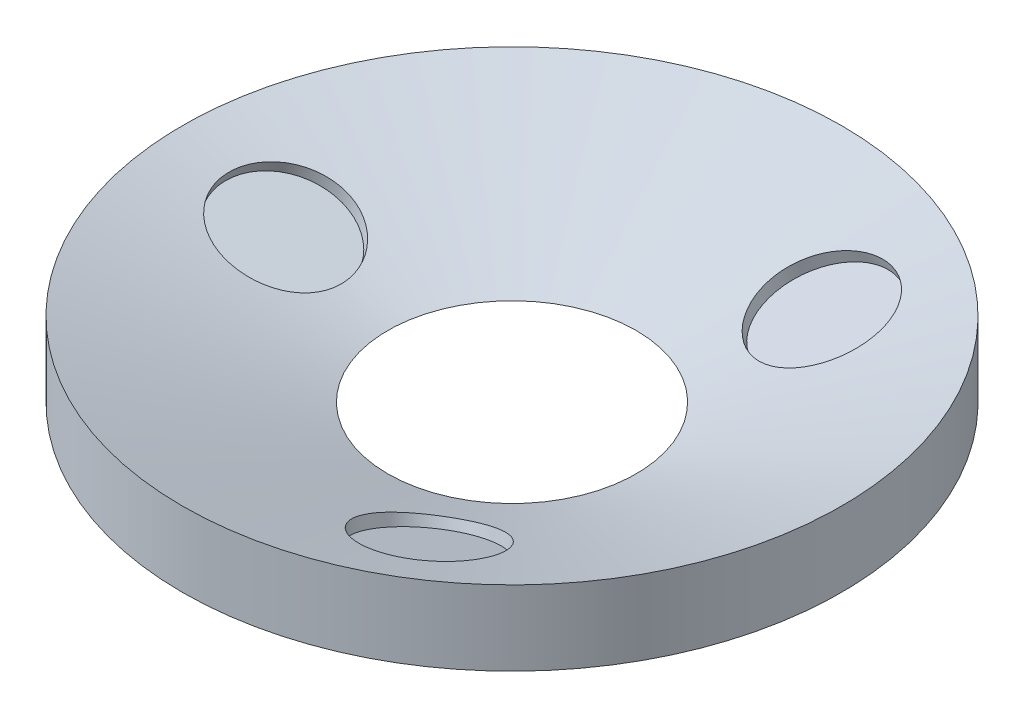
SolidWorks part; units mm, degrees
material "HDPE"
ref_plane "Piano frontale" through (0, 0, 0) normal (0, 0, 1) x (1, 0, 0)
ref_plane "Piano superiore" through (0, 0, 0) normal (0, 1, 0) x (1, 0, 0)
ref_plane "Piano destro" through (0, 0, 0) normal (1, 0, 0) x (0, 0, -1)
sketch "Schizzo1" plane through (0, 0, 0) normal (0, 0, 1) x (1, 0, 0)
  line L0 (-69, 15.6507) -> (-69, 0)
  line L1 (-69, 0) -> (-26, 0)
  line L2 (-26, 0) -> (-69, 15.6507)
  line L3 (0, 0) -> (0, 150.3289) construction
  dimension "D1" = 43
  dimension "D2" = 20
  dimension "D3" = 52
revolve "Rivoluzione1" add sketch "Schizzo1" angle 360 about L3
ref_plane "Piano1" through (-3.0414, -8.3562, 0) normal (0.342, 0.9397, 0) x (-0.9397, 0.342, 0)
sketch "Schizzo2" plane through (-3.0414, -8.3562, 0) normal (0.342, 0.9397, 0) x (-0.9397, 0.342, 0)
  line L0 (24.432, 0) -> (70.1917, 0) construction
  circle A0 centre (47.3118, 0) radius 12.5
  dimension "D1" = 25
extrude "Taglio-Estrusione5" cut sketch "Schizzo2" against normal blind 2 and the other way blind 10 contours A0
pattern_circular "RipetizioneCircolare1" count 3 every 120 about axis through (0, 0, 0) along (0, 1, 0) of "Taglio-Estrusione5"
